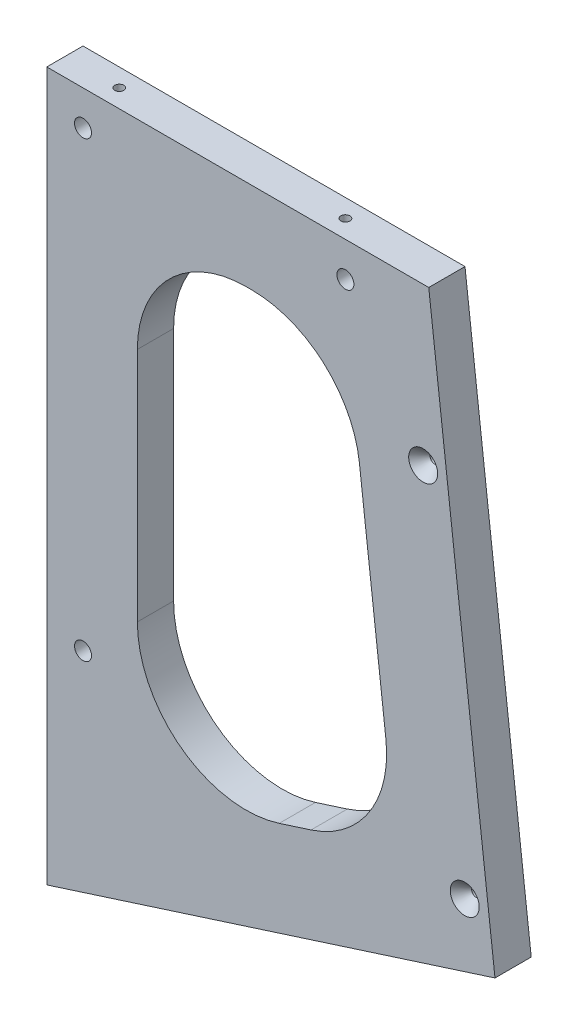
SolidWorks part; units mm, degrees
material "Beech"
ref_plane "Front Plane" through (0, 0, 0) normal (0, 0, 1) x (1, 0, 0)
ref_plane "Top Plane" through (0, 0, 0) normal (0, 1, 0) x (1, 0, 0)
ref_plane "Right Plane" through (0, 0, 0) normal (1, 0, 0) x (0, 0, -1)
sketch "Sketch1" plane through (0, 0, 0) normal (0, 0, 1) x (1, 0, 0)
  line L1 (-222.053, -248.25) -> (-222.053, 0) construction
  line L2 (-88.1902, 0) -> (-222.053, 0)
  line L3 (-222.053, -248.25) -> (-222.053, 0)
  line L4 (-91.9973, 0) -> (-234.753, 0) construction
  line L7 (-64.9774, -197.966) -> (-88.1902, 0)
  line L8 (-64.9774, -197.966) -> (-222.053, -248.25)
extrude "Boss-Extrude1" add sketch "Sketch1" against normal blind 12.7
hole_wizard "Hole1" positions "Sketch2" profile "Sketch3" legacy
sketch "Sketch2" plane through (181.0394, 12.7, 123.1167) normal (0, 1, 0) x (0, 0, -1)
  line L0 (-129.4667, 415.7924) -> (-129.4667, 273.0368) construction
  line L5 (-135.8167, 409.4424) -> (135.5488, 409.4424) construction
  line L10 (-135.8167, 279.3868) -> (135.5488, 279.3868) construction
  line L11 (-0.134, 409.4424) -> (-0.134, 279.3868) construction
  point P22 (-129.4667, 384.0424)
  point P24 (-129.4667, 304.7868)
  point P26 (-110.4167, 409.4424)
  point P30 (-0.134, 409.4424)
  point P50 (110.1488, 409.4424)
  point P51 (129.1988, 304.7868)
  point P52 (129.1988, 384.0424)
sketch "Sketch3" plane through (-203.003, 12.7, -6.082) normal (1, 0, 0) x (0, 0, 1)
  line L0 (0, 0) -> (0, 32.7039)
  line L1 (0, 32.7039) -> (1.5875, 31.75)
  line L2 (1.5875, 31.75) -> (1.5875, 4.0177)
  line L3 (1.5875, 4.0177) -> (5.08, 0)
  line L4 (5.08, 0) -> (0, 0)
  line L5 (0, -14.3089) -> (0, 102.4216) construction
  line L6 (0, 32.7039) -> (-1.5875, 31.75) construction
  line L7 (-1.5875, 4.0177) -> (-5.08, 0) construction
  dimension "Diameter" = 3.175
  dimension "Depth" = 31.75
  dimension "C-Sink Diameter" = 10.16
  dimension "C-Sink Angle" = 82
  dimension "Drill Angle" = 118
hole_wizard "Hole3" positions "Sketch6" profile "Sketch7" legacy
sketch "Sketch6" plane through (-234.753, 1073.3642, -135.8167) normal (-1, 0, 0) x (0, 0, -1)
  line L3 (-0.134, 1338.7628) -> (-0.134, 1090.5128) construction
  point P1 (-129.4667, 1300.6628)
  point P3 (-129.4667, 1128.6128)
  point P15 (129.1988, 1128.6128)
  point P16 (129.1988, 1300.6628)
sketch "Sketch7" plane through (-234.753, -227.2986, -6.35) normal (0, 1, 0) x (0, 0, 1)
  line L0 (0, 0) -> (0, 32.7039)
  line L1 (0, 32.7039) -> (1.5875, 31.75)
  line L2 (1.5875, 31.75) -> (1.5875, 4.0177)
  line L3 (1.5875, 4.0177) -> (5.08, 0)
  line L4 (5.08, 0) -> (0, 0)
  line L5 (0, -14.3089) -> (0, 102.4216) construction
  line L6 (0, 32.7039) -> (-1.5875, 31.75) construction
  line L7 (-1.5875, 4.0177) -> (-5.08, 0) construction
  dimension "Diameter" = 3.175
  dimension "Depth" = 31.75
  dimension "C-Sink Diameter" = 10.16
  dimension "C-Sink Angle" = 82
  dimension "Drill Angle" = 118
hole_wizard "Hole5" positions "Sketch10" profile "Sketch11" legacy
sketch "Sketch10" plane through (-234.753, 1090.5128, 123.1167) normal (-1, 0, 0) x (0, 0, -1)
  line L3 (-0.134, 1338.7628) -> (-0.134, 1090.5128) construction
  point P1 (-129.4667, 1300.6628)
  point P3 (-129.4667, 1128.6128)
  point P15 (129.1988, 1128.6128)
  point P16 (129.1988, 1300.6628)
sketch "Sketch11" plane through (-234.753, -210.15, 252.5835) normal (0, 1, 0) x (0, 0, 1)
  line L0 (0, 0) -> (0, 32.7039)
  line L1 (0, 32.7039) -> (1.5875, 31.75)
  line L2 (1.5875, 31.75) -> (1.5875, 4.0177)
  line L3 (1.5875, 4.0177) -> (5.08, 0)
  line L4 (5.08, 0) -> (0, 0)
  line L5 (0, -14.3089) -> (0, 102.4216) construction
  line L6 (0, 32.7039) -> (-1.5875, 31.75) construction
  line L7 (-1.5875, 4.0177) -> (-5.08, 0) construction
  dimension "Diameter" = 3.175
  dimension "Depth" = 31.75
  dimension "C-Sink Diameter" = 10.16
  dimension "C-Sink Angle" = 82
  dimension "Drill Angle" = 118
hole_wizard "Hole6" positions "Sketch12" profile "Sketch13" legacy
sketch "Sketch12" plane through (181.0394, 1073.3642, 0) normal (0, 0, 1) x (-0.9272, -0.3746, 0)
  point P29 (707.1666, 1065.2704)
  point P31 (674.128, 944.6031)
sketch "Sketch13" plane through (-75.5767, -179.2465, 0) normal (1, 0, 0) x (0, -1, 0)
  line L0 (0, 0) -> (0, 39.0539)
  line L1 (0, 39.0539) -> (1.5875, 38.1)
  line L2 (1.5875, 38.1) -> (1.5875, 4.0177)
  line L3 (1.5875, 4.0177) -> (5.08, 0)
  line L4 (5.08, 0) -> (0, 0)
  line L5 (0, -14.3089) -> (0, 102.4216) construction
  line L6 (0, 39.0539) -> (-1.5875, 38.1) construction
  line L7 (-1.5875, 4.0177) -> (-5.08, 0) construction
  dimension "Diameter" = 3.175
  dimension "Depth" = 38.1
  dimension "C-Sink Diameter" = 10.16
  dimension "C-Sink Angle" = 82
  dimension "Drill Angle" = 118
hole_wizard "Hole7" positions "Sketch14" profile "Sketch15" legacy
sketch "Sketch14" plane through (181.0394, 12.7, -135.8167) normal (0, 1, 0) x (0, 0, -1)
  line L0 (-129.4667, 415.7924) -> (-129.4667, 273.0368) construction
  line L5 (-135.8167, 409.4424) -> (135.5488, 409.4424) construction
  line L10 (-135.8167, 279.3868) -> (135.5488, 279.3868) construction
  line L11 (-0.134, 409.4424) -> (-0.134, 279.3868) construction
  point P22 (-129.4667, 384.0424)
  point P24 (-129.4667, 304.7868)
  point P26 (-110.4167, 409.4424)
  point P30 (-0.134, 409.4424)
  point P50 (110.1488, 409.4424)
  point P51 (129.1988, 304.7868)
  point P52 (129.1988, 384.0424)
sketch "Sketch15" plane through (-203.003, 12.7, -265.0155) normal (1, 0, 0) x (0, 0, 1)
  line L0 (0, 0) -> (0, 32.7039)
  line L1 (0, 32.7039) -> (1.5875, 31.75)
  line L2 (1.5875, 31.75) -> (1.5875, 4.0177)
  line L3 (1.5875, 4.0177) -> (5.08, 0)
  line L4 (5.08, 0) -> (0, 0)
  line L5 (0, -14.3089) -> (0, 102.4216) construction
  line L6 (0, 32.7039) -> (-1.5875, 31.75) construction
  line L7 (-1.5875, 4.0177) -> (-5.08, 0) construction
  dimension "Diameter" = 3.175
  dimension "Depth" = 31.75
  dimension "C-Sink Diameter" = 10.16
  dimension "C-Sink Angle" = 82
  dimension "Drill Angle" = 118
hole_wizard "Hole8" positions "Sketch16" profile "Sketch17" legacy
sketch "Sketch16" plane through (531.1976, -20.4499, -135.8167) normal (0.3049, -0.9524, 0) x (0, 0, 1)
  line L0 (129.4667, 798.9359) -> (129.4667, 624.9146) construction
  line L5 (0.134, 798.9359) -> (0, 625.1618) construction
  point P10 (129.4667, 663.0146)
  point P12 (129.4667, 760.8359)
  point P20 (-129.4082, 663.2142)
  point P21 (-129.2574, 761.0354)
sketch "Sketch17" plane through (-193.6044, -252.4777, -265.0741) normal (0, 0, 1) x (0.9524, 0.3049, 0)
  line L0 (0, 0) -> (0, 32.7039)
  line L1 (0, 32.7039) -> (1.5875, 31.75)
  line L2 (1.5875, 31.75) -> (1.5875, 4.0177)
  line L3 (1.5875, 4.0177) -> (5.08, 0)
  line L4 (5.08, 0) -> (0, 0)
  line L5 (0, -14.3089) -> (0, 102.4216) construction
  line L6 (0, 32.7039) -> (-1.5875, 31.75) construction
  line L7 (-1.5875, 4.0177) -> (-5.08, 0) construction
  dimension "Diameter" = 3.175
  dimension "Depth" = 31.75
  dimension "C-Sink Diameter" = 10.16
  dimension "C-Sink Angle" = 82
  dimension "Drill Angle" = 118
hole_wizard "15/64 (0.23438) Diameter Hole1" positions "Sketch18" profile "Sketch19" hole size "15/64" standard "ANSI Inch" end condition through all
sketch "Sketch18" plane through (0, 0, 0) normal (0, 0, 1) x (1, 0, 0)
  point P0 (-117.3973, -12.1795)
  point P2 (-209.353, -12.1795)
sketch "Sketch19" plane through (-117.3973, -12.1795, 0) normal (1, 0, 0) x (0, -1, 0)
  line L0 (0, 0) -> (0, 12.7)
  line L1 (0, 12.7) -> (2.9766, 12.7)
  line L2 (2.9766, 12.7) -> (2.9766, 0)
  line L5 (2.9766, 0) -> (0, 0)
  line L11 (0, -6.35) -> (0, 107.95) construction
  dimension "Thru Hole Dia." = 5.9533
  dimension "Thru Hole Depth" = 12.7
hole_wizard "15/64 (0.23438) Diameter Hole2" positions "Sketch20" profile "Sketch21" hole size "15/64" standard "ANSI Inch" end condition through all
sketch "Sketch20" plane through (0, 0, 0) normal (0, 0, 1) x (1, 0, 0)
  point P0 (-209.353, -170.8461)
sketch "Sketch21" plane through (-209.353, -170.8461, 0) normal (1, 0, 0) x (0, -1, 0)
  line L0 (0, 0) -> (0, 12.7)
  line L1 (0, 12.7) -> (2.9766, 12.7)
  line L2 (2.9766, 12.7) -> (2.9766, 0)
  line L5 (2.9766, 0) -> (0, 0)
  line L11 (0, -6.35) -> (0, 107.95) construction
  dimension "Thru Hole Dia." = 5.9533
  dimension "Thru Hole Depth" = 12.7
sketch "Sketch22" plane through (0, 0, 0) normal (0, 0, 1) x (1, 0, 0)
  line L8 (-99.556, -175.6983) -> (-116.4348, -31.75)
  line L9 (-116.4348, -31.75) -> (-190.303, -31.75)
  line L10 (-190.303, -31.75) -> (-190.303, -204.7488)
  line L11 (-190.303, -204.7488) -> (-99.556, -175.6983)
  line L12 (-99.556, -175.6983) -> (-116.4348, -31.75)
  line L13 (-116.4348, -31.75) -> (-190.303, -31.75)
  line L14 (-190.303, -31.75) -> (-190.303, -204.7488)
  line L15 (-190.303, -204.7488) -> (-99.556, -175.6983)
  dimension "D1" = 31.75
extrude "Cut-Extrude1" cut sketch "Sketch22" against normal through all
fillet "Fillet1" radius 38.1 4 edges at (-99.556, -175.6983, -6.35) (-116.4348, -31.75, -6.35) (-190.303, -31.75, -6.35) (-190.303, -204.7488, -6.35)
